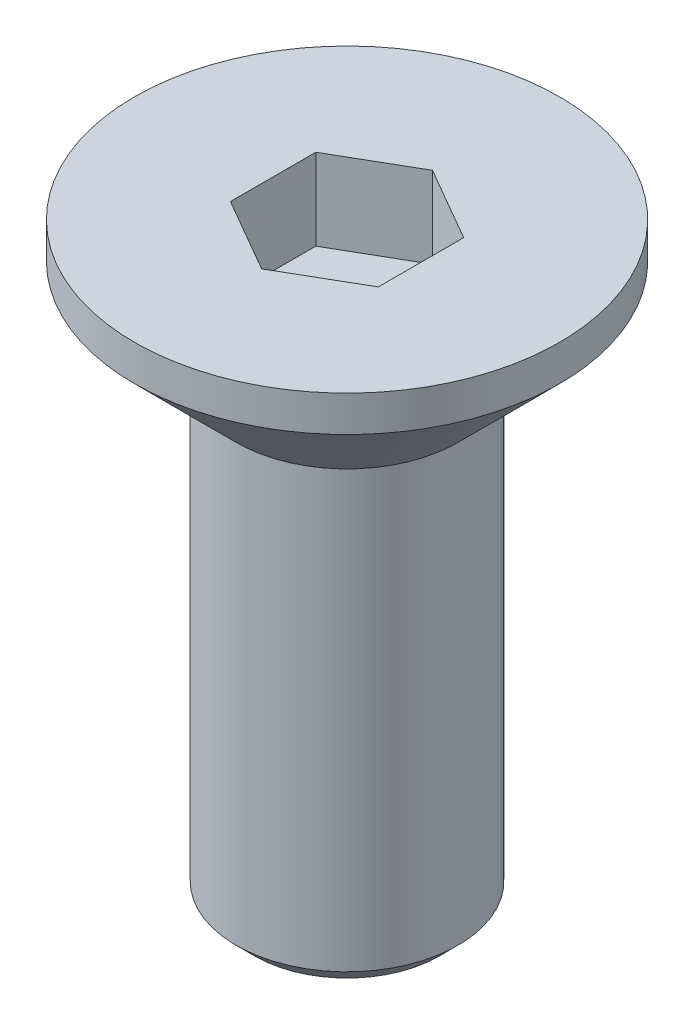
SolidWorks part; units mm, degrees
material "ASTM A36 Steel"
ref_plane "Front Plane" through (0, 0, 0) normal (0, 0, 1) x (1, 0, 0)
ref_plane "Top Plane" through (0, 0, 0) normal (0, 1, 0) x (1, 0, 0)
ref_plane "Right Plane" through (0, 0, 0) normal (1, 0, 0) x (0, 0, -1)
sketch "Sketch1" plane through (0, 0, 0) normal (0, 0, 1) x (1, 0, 0)
  line L0 (0, 0) -> (0, -8)
  line L1 (0, 0) -> (-2.875, 0)
  line L2 (-2.875, -0.485) -> (-1.5, -1.86)
  line L3 (-1.5, -1.86) -> (-1.5, -7.75)
  line L4 (-1.25, -8) -> (0, -8)
  line L5 (-2.875, 0) -> (-2.875, -0.485)
  line L6 (-1.5, -7.75) -> (-1.25, -8)
  point P6 (-1.5, -8)
  dimension "D1" = 1.86
  dimension "D2" = 2.875
  dimension "D3" = 1.5
  dimension "D4" = 45
  dimension "D5" = 8
revolve "Revolve1" add sketch "Sketch1" angle 360 about L0
sketch "Sketch2" plane through (0, 0, 0) normal (0, 1, 0) x (1, 0, 0)
  line L1 (-1, 0.5774) -> (-1, -0.5774)
  line L2 (-1, -0.5774) -> (0, -1.1547)
  line L3 (0, -1.1547) -> (1, -0.5774)
  line L4 (1, -0.5774) -> (1, 0.5774)
  line L5 (1, 0.5774) -> (0, 1.1547)
  line L6 (0, 1.1547) -> (-1, 0.5774)
  circle A0 centre (0, 0) radius 1 construction
  dimension "D1" = 2
extrude "Cut-Extrude1" cut sketch "Sketch2" against normal blind 1.1
